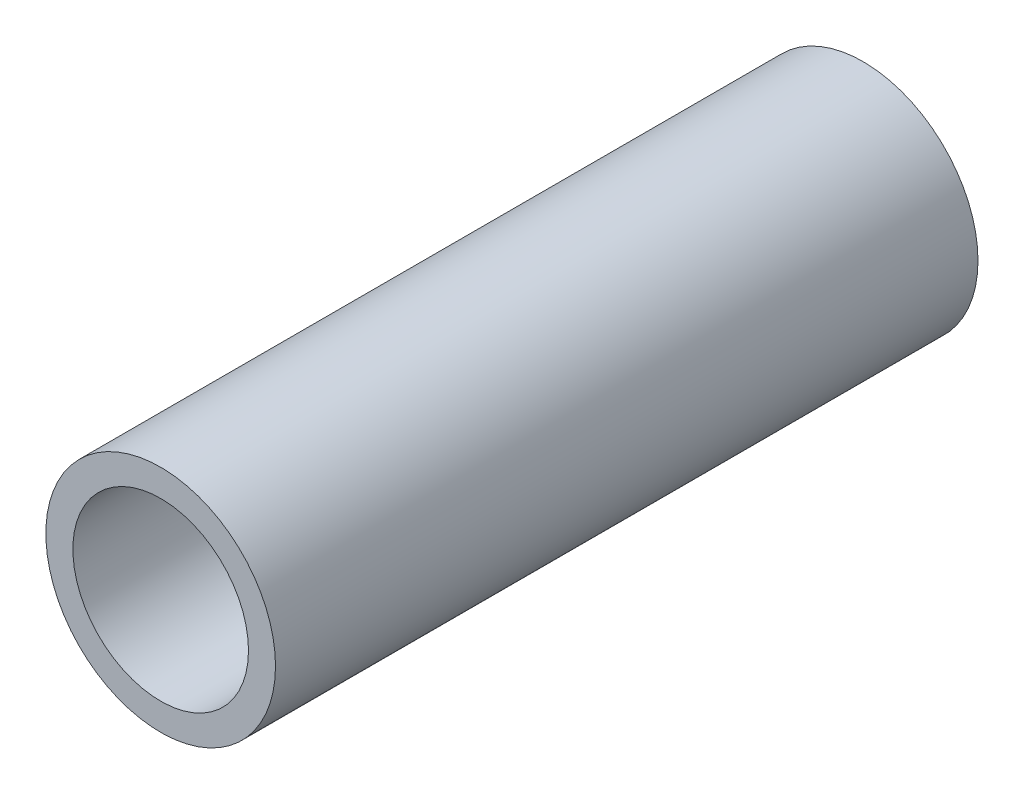
SolidWorks part; units mm, degrees
ref_plane "Plan1" through (0, 0, 0) normal (0, 0, 1) x (1, 0, 0)
ref_plane "Plan2" through (0, 0, 0) normal (0, 1, 0) x (1, 0, 0)
ref_plane "Plan3" through (0, 0, 0) normal (1, 0, 0) x (0, 0, -1)
sketch "Esquisse1" plane through (0, 0, 0) normal (0, 0, 1) x (1, 0, 0)
  circle A0 centre (0, 0) radius 8.5
  circle A1 centre (0, 0) radius 6.5
  dimension "D1" = 17
  dimension "D2" = 13
extrude "Base-Extrusion" add sketch "Esquisse1" along normal blind 52
